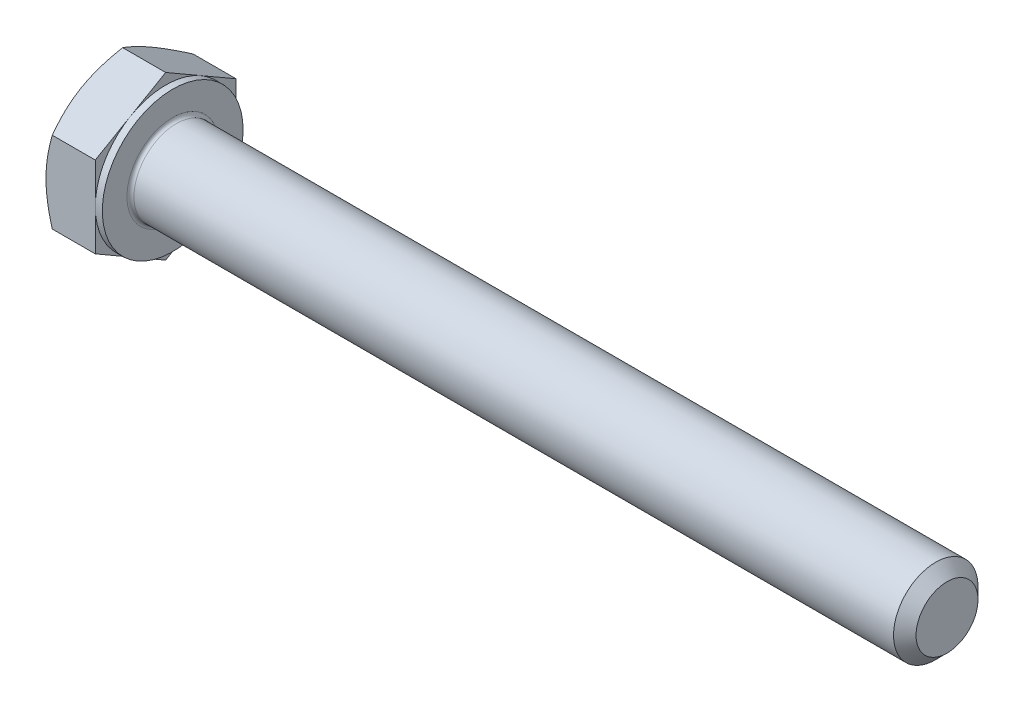
SolidWorks part; units mm, degrees
extrude "基体-拉伸" add sketch "草图1" along normal blind 4
sketch "草图1" plane through (0, 0, 0) normal (1, 0, 0) x (0, 0, -1)
  line L0 (5, 2.8868) -> (5, -2.8868)
  line L1 (-5, 2.8868) -> (-5, -2.8868)
  line L2 (5, -2.8868) -> (0, -5.7735)
  line L3 (0, -5.7735) -> (-5, -2.8868)
  line L4 (5, 2.8868) -> (0, 5.7735)
  line L5 (0, 5.7735) -> (-5, 2.8868)
  dimension "s" = 10
  dimension "D2" = 120
  dimension "D3" = 5
  dimension "D4" = 5
  dimension "D5" = 5
revolve "切除-旋转1" cut sketch "草图3" angle 360 about L6
sketch "草图3" plane through (0, 0, 0) normal (0, 0, 1) x (1, 0, 0)
  line L0 (0, 5) -> (3.3333, 10.7735)
  line L1 (0, 5.7735) -> (0, 2.8868) construction
  line L2 (3.3333, 10.7735) -> (3.3333, 15.7735)
  line L3 (3.3333, 15.7735) -> (-10, 15.7735)
  line L4 (-10, 15.7735) -> (-10, 5)
  line L5 (-10, 5) -> (0, 5)
  line L6 (0, 0) -> (99.06, 0) construction
  line L7 (4, 5.7735) -> (0, 5.7735) construction
  dimension "D4" = 5
  dimension "D1" = 5
  dimension "D2" = 5
  dimension "D3" = 10
  dimension "Head_ch_ang" = 30
material "3.6级"
ref_plane "前视" through (0, 0, 0) normal (0, 0, 1) x (1, 0, 0)
ref_plane "上视" through (0, 0, 0) normal (0, 1, 0) x (1, 0, 0)
ref_plane "右视" through (0, 0, 0) normal (1, 0, 0) x (0, 0, -1)
sketch "草图2" plane through (0, 0, 0) normal (0, 0, 1) x (1, 0, 0)
  line L0 (0, 2.8868) -> (0, -2.8868) construction
  line L1 (0, 0) -> (59, 0)
  line L2 (0, 0) -> (0, 3)
  line L3 (0, 3) -> (27.8072, 3)
  line L4 (59, 0) -> (59, 2.134)
  line L5 (4, 5.7735) -> (4, 2.8868) construction
  line L7 (0, 0) -> (96.52, 0) construction
  line L8 (59, -2.134) -> (27.8072, -3) construction
  line L9 (0, -3) -> (27.8072, -3) construction
  line L10 (5, 15.24) -> (5, -1.27) construction
  line L11 (41, 15.24) -> (41, -1.27) construction
  line L12 (4, 2.8868) -> (4, -2.8868) construction
  line L13 (27.8072, 3) -> (59, 3)
  line L14 (59, 3) -> (59, 2.134)
revolve "凸台-旋转1" add sketch "草图2" angle 360 about L7
cosmetic thread "螺旋线1" parameters "Thread_length"=18, "Thread_minor"=4.268
sketch "草图5" plane through (0, 0, 0) normal (0, 0, 1) x (1, 0, 0)
  line L0 (4, 5) -> (0.6667, 10.7735)
  line L1 (4, 5.7735) -> (4, 2.8868) construction
  line L2 (0.6667, 10.7735) -> (0.6667, 15.7735)
  line L3 (0.6667, 15.7735) -> (10.6667, 15.7735)
  line L4 (10.6667, 15.7735) -> (10.6667, 5)
  line L5 (10.6667, 5) -> (4, 5)
  line L7 (4, 5.7735) -> (0.4466, 5.7735) construction
  line L8 (0, 0) -> (99.06, 0) construction
  line L9 (0, 0) -> (99.06, 0) construction
  dimension "D4" = 5
  dimension "D1" = 5
  dimension "D2" = 5
  dimension "D3" = 10
  dimension "Head_ch_ang" = 30
revolve "切除-旋转2" cut sketch "草图5" angle 360 about L8
sketch "草图4" plane through (0, 0, 0) normal (0, 0, 1) x (1, 0, 0)
  line L1 (4, 5.7735) -> (4, 2.8868) construction
  line L2 (4, 5) -> (3.5, 5)
  line L3 (4, 5) -> (4, 15.7735)
  line L4 (4, 15.7735) -> (3.5, 15.7735)
  line L5 (0, 0) -> (95.25, 0) construction
  line L6 (0, 0) -> (96.52, 0) construction
  line L7 (3.5, 5) -> (3.5, 15.7735)
  line L8 (3.5534, 5.7735) -> (0.4466, 5.7735) construction
  dimension "D2" = 10
  dimension "D1" = 10
revolve "切除-旋转3" cut sketch "草图4" angle 360 about L5
chamfer "倒角" distance 0.8 angle 45 1 edges at (59, 0, 3)
fillet "圆角" radius 0.25 1 edges at (4, 0, -3)
sketch "草图6" plane through (0, 0, 0) normal (0, 0, 1) x (1, 0, 0)
  line L0 (41, -2.134) -> (40.5, -3)
  line L1 (41, -2.134) -> (41.5, -3)
  line L2 (41.5, -3) -> (41.5, -3.75)
  line L3 (-3.175, 0) -> (5.1513, 0) construction
  line L5 (41.5, -3.75) -> (40.5, -3.75)
  line L6 (40.5, -3.75) -> (40.5, -3)
  dimension "Thread_minor" = 4.268
  dimension "Diameter" = 6
  dimension "Start" = 41
revolve "切除-旋转4" [suppressed] cut sketch "草图6" angle 360 about L3
pattern_linear "阵列(线性)1" [suppressed]
equation "\"D3@草图1\" = \"s@草图1\" / 2"
equation "\"D4@草图1\" = \"D3@草图1\""
equation "\"D5@草图1\" = \"D4@草图1\""
equation "\"Thread_minor@螺旋线1\" = \"Minor_dia@草图2\""
equation "\"D1@草图3\" = \"s@草图1\" / 2"
equation "\"D1@草图5\" = \"s@草图1\" / 2"
equation "\"Head_ch_ang@草图5\" = \"Head_ch_ang@草图3\""
equation "\"D1@草图4\" = \"s@草图1\""
equation "\"Thread_length@螺旋线1\" = ((sgn( (\"l@草图2\" - \"p@草图2\" ) - \"h@草图2\" )-1)*( (\"l@草图2\" - \"p@草图2\" ) - \"h@草图2\" ))/-2+ \"h@草图2\""
equation "\"Thread_minor@草图6\" = \"Minor_dia@草图2\""
equation "\"Diameter@草图6\" = \"m@草图2\""
equation "\"Overcut@草图6\" = \"m@草图2\" * 1.25"
equation "\"Start@草图6\" = \"k@基体-拉伸\" + \"l@草图2\" - \"Thread_length@螺旋线1\"  '---Non-countersunk---"
equation "\"Num_threads@阵列(线性)1\" = int( \"Thread_length@螺旋线1\" / \"p@草图2\" + 0.999 )  + 1"
equation "\"Advance@阵列(线性)1\" = \"Thread_length@螺旋线1\" /  (\"Num_threads@阵列(线性)1\" - 1) 'relax it"
equation "\"Num_threads@阵列(线性)1\" = \"Num_threads@阵列(线性)1\" - sgn( \"Num_threads@阵列(线性)1\" - 1) '---chamfered tips only---"
equation "\"Minor_dia@草图2\" = \"m@草图2\"-\"p@草图2\" * 1.732"
equation "\"D1@倒角\" = \"p@草图2\"*0.8"
